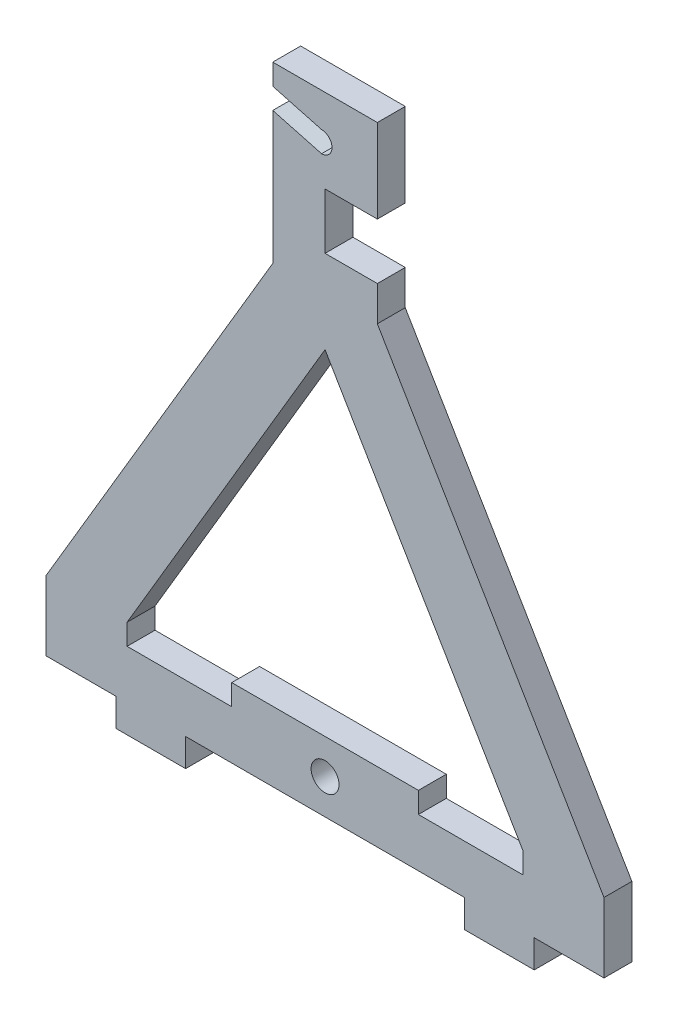
SolidWorks part; units mm, degrees
ref_plane "Front Plane" through (0, 0, 0) normal (0, 0, 1) x (1, 0, 0)
ref_plane "Top Plane" through (0, 0, 0) normal (0, 1, 0) x (1, 0, 0)
ref_plane "Right Plane" through (0, 0, 0) normal (1, 0, 0) x (0, 0, -1)
sketch "Sketch1" plane through (0, 0, 0) normal (0, 0, 1) x (1, 0, 0)
  line L0 (-80, 0) -> (80, 0)
  line L1 (80, 0) -> (80, 20)
  line L2 (80, 20) -> (15, 130)
  line L3 (-15, 130) -> (-80, 20)
  line L4 (-80, 20) -> (-80, 0)
  line L5 (0, 0) -> (0, 180) construction
  line L6 (15, 180) -> (-15, 180)
  line L7 (-15, 180) -> (-15, 130)
  line L8 (15, 180) -> (15, 130)
  line L9 (80, 20) -> (-80, 20) construction
  line L10 (-15, 130) -> (15, 130) construction
  line L11 (-56.7692, 20) -> (0, 116.071)
  line L12 (0, 116.071) -> (56.7692, 20)
  line L13 (56.7692, 20) -> (-56.7692, 20)
  line L14 (-56.7692, 20) -> (-56.7692, 0) construction
  line L15 (56.7692, 20) -> (56.7692, 0) construction
  circle A3 centre (0, 10) radius 4
  point P4 (0, 0)
  point P13 (0, 180)
  dimension "D7" = 10
  dimension "D10" = 8
  dimension "D1" = 160
  dimension "D2" = 50
  dimension "D3" = 130
  dimension "D4" = 30
  dimension "D5" = 20
  dimension "D6" = 20
extrude "Boss-Extrude1" add sketch "Sketch1" along normal blind 8
sketch "Sketch2" plane through (0, 0, 0) normal (0, -1, 0) x (1, 0, 0)
  line L0 (-80, 8) -> (80, 8) construction
  line L1 (-60, 8) -> (-40, 8)
  line L2 (-60, 8) -> (-60, 0)
  line L3 (-60, 0) -> (-40, 0)
  line L4 (-40, 8) -> (-40, 0)
  line L5 (-80, 0) -> (80, 0) construction
  line L6 (-80, 8) -> (-80, 0) construction
  dimension "D1" = 20
  dimension "D2" = 20
extrude "Boss-Extrude2" add sketch "Sketch2" along normal blind 8
mirror "Mirror1" about plane through (0, 0, 0) normal (1, 0, 0) of "Boss-Extrude2"
sketch "Sketch4" plane through (0, 0, 8) normal (0, 0, 1) x (1, 0, 0)
  line L0 (15, 130) -> (15, 180) construction
  line L1 (15, 156) -> (0, 156)
  line L2 (15, 156) -> (15, 140)
  line L3 (15, 140) -> (0, 140)
  line L4 (0, 156) -> (0, 140)
  line L6 (15, 130) -> (-15, 130) construction
  line L7 (80, 20) -> (15, 130) construction
  dimension "D1" = 10
  dimension "D2" = 16
  dimension "D3" = 15
extrude "Cut-Extrude1" cut sketch "Sketch4" against normal blind 10
sketch "Sketch5" plane through (0, 0, 8) normal (0, 0, 1) x (1, 0, 0)
  line L1 (-56.7692, 20) -> (-26.7692, 20)
  line L2 (-56.7692, 20) -> (-56.7692, 14)
  line L3 (-56.7692, 14) -> (-26.7692, 14)
  line L4 (-26.7692, 20) -> (-26.7692, 14)
  point P5 (-26.7692, 17)
  dimension "D1" = 6
  dimension "D2" = 30
extrude "Cut-Extrude2" cut sketch "Sketch5" against normal blind 8
mirror "Mirror2" about plane through (0, 0, 0) normal (1, 0, 0) of "Cut-Extrude2"
sketch "Sketch7" plane through (0, 0, 8) normal (0, 0, 1) x (1, 0, 0)
  line L2 (-15, 174) -> (-1, 170.2487)
  line L3 (-15, 180) -> (-15, 130) construction
  line L5 (-1, 164.2487) -> (-15, 168)
  line L6 (-15, 168) -> (-15, 174)
  line L7 (15, 180) -> (-15, 180) construction
  line L8 (-1, 164.2487) -> (-1, 170.2487) construction
  arc A1 (-1, 164.2487) -> (-1, 170.2487) centre (-1, 167.2487) ccw
  point P4 (0, 0)
  dimension "D1" = 6
  dimension "D5" = 3
  dimension "D2" = 6
  dimension "D3" = 14
  dimension "D4" = 75
extrude "Cut-Extrude4" cut sketch "Sketch7" against normal through all
